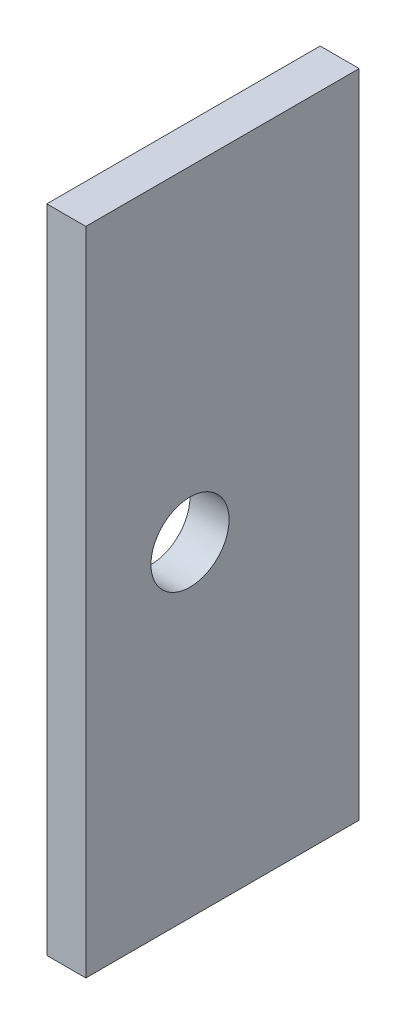
SolidWorks part; units mm, degrees
material "Commercially Pure CP-Ti UNS R50400 (SS)"
ref_plane "Front Plane" through (0, 0, 0) normal (0, 0, 1) x (1, 0, 0)
ref_plane "Top Plane" through (0, 0, 0) normal (0, 1, 0) x (1, 0, 0)
ref_plane "Right Plane" through (0, 0, 0) normal (1, 0, 0) x (0, 0, -1)
sketch "Sketch1" plane through (0, 0, 0) normal (1, 0, 0) x (0, 0, -1)
  line L1 (0, 0) -> (2.1, 0)
  line L2 (0, 0) -> (0, 5)
  line L3 (0, 5) -> (2.1, 5)
  line L4 (2.1, 0) -> (2.1, 5)
  dimension "D1" = 2.1
  dimension "D2" = 5
extrude "Boss-Extrude1" add sketch "Sketch1" along normal blind 0.3
hole_wizard "Ø0.6 (0.6) Diameter Hole1" positions "Sketch3" profile "Sketch2" hole size "Ø0.6" standard "ISO" end condition through all
sketch "Sketch3" plane through (0.3, 0, 0) normal (1, 0, 0) x (0, 0, -1)
  line L1 (0, 0) -> (2.1, 0) construction
  line L2 (0, 5) -> (0, 0) construction
  point P0 (0.8, 2.5)
  dimension "D1" = 0.8
  dimension "D2" = 2.5
sketch "Sketch2" plane through (0.3, 2.5, -0.8) normal (0, 1, 0) x (0, 0, -1)
  line L0 (0, 0) -> (0, 0.3)
  line L1 (0, 0.3) -> (0.3, 0.3)
  line L2 (0.3, 0.3) -> (0.3, 0)
  line L5 (0.3, 0) -> (0, 0)
  line L11 (0, -6.35) -> (0, 107.95) construction
  dimension "Thru Hole Dia." = 0.6
  dimension "Thru Hole Depth" = 0.3
